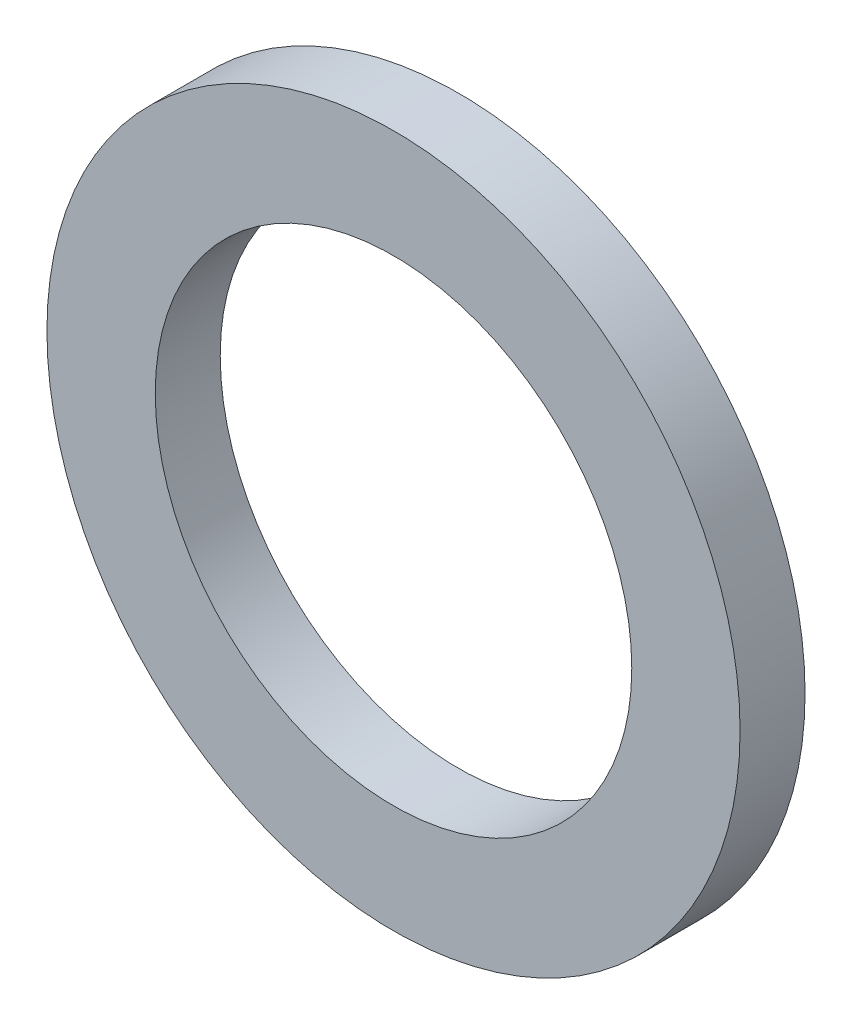
SolidWorks part; units mm, degrees
material "ABS"
ref_plane "前视基准面" through (0, 0, 0) normal (0, 0, 1) x (1, 0, 0)
ref_plane "上视基准面" through (0, 0, 0) normal (0, 1, 0) x (1, 0, 0)
ref_plane "右视基准面" through (0, 0, 0) normal (1, 0, 0) x (0, 0, -1)
sketch "Sketch1" plane through (0, 0, 0) normal (0, 0, 1) x (1, 0, 0)
  circle A0 centre (0, 0) radius 8
  circle A1 centre (0, 0) radius 5.5
  dimension "D1" = 11
  dimension "D2" = 16
extrude "Extrude1" add sketch "Sketch1" along normal blind 1.5
